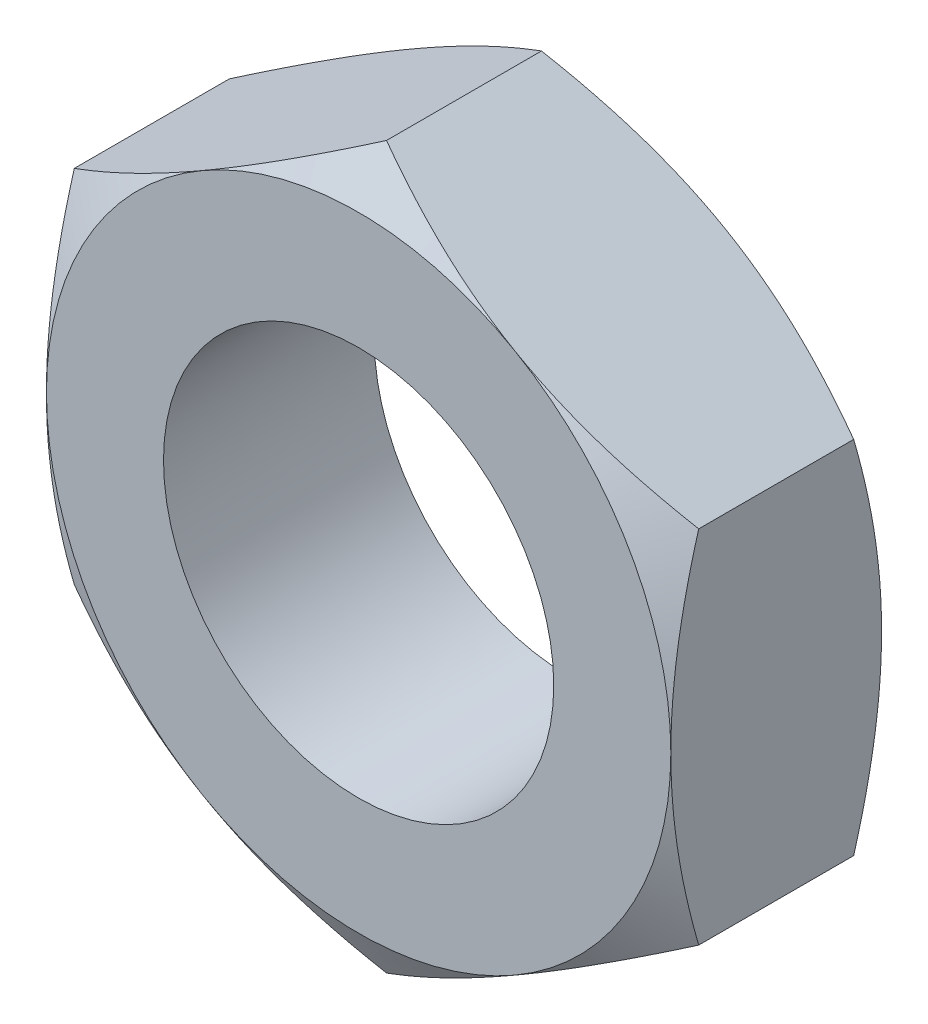
SolidWorks part; units mm, degrees
material "1.4000 (X6Cr13)"
ref_plane "Płaszczyzna przednia" through (0, 0, 0) normal (0, 0, 1) x (1, 0, 0)
ref_plane "Płaszczyzna górna" through (0, 0, 0) normal (0, 1, 0) x (1, 0, 0)
ref_plane "Płaszczyzna prawa" through (0, 0, 0) normal (1, 0, 0) x (0, 0, -1)
sketch "Szkic1" plane through (0, 0, 0) normal (0, 0, 1) x (1, 0, 0)
  line L1 (-4, 2.3094) -> (-4, -2.3094)
  line L2 (-4, -2.3094) -> (0, -4.6188)
  line L3 (0, -4.6188) -> (4, -2.3094)
  line L4 (4, -2.3094) -> (4, 2.3094)
  line L5 (4, 2.3094) -> (0, 4.6188)
  line L6 (0, 4.6188) -> (-4, 2.3094)
  circle A0 centre (0, 0) radius 2.5
  circle A1 centre (0, 0) radius 4 construction
  dimension "d" = 5
  dimension "s" = 8
extrude "Dodanie-wyciągnięcie1" add sketch "Szkic1" along normal mid plane 2.7
sketch "Szkic2" plane through (0, 0, 1.35) normal (0, 0, 1) x (1, 0, 0)
  circle A0 centre (0, 0) radius 4
  dimension "D1" = 8
extrude "Wytnij-wyciągnięcie2" cut sketch "Szkic2" against normal blind 2.7 draft 60 flip side to cut
mirror "Lustro1" about plane through (0, 0, 0) normal (0, 0, 1) of "Wytnij-wyciągnięcie2"
equation "\"D1@Szkic2\" = \"s@Szkic1\""
equation "\"D1@Wytnij-wyciągnięcie2\" = \"m@Dodanie-wyciągnięcie1\""
